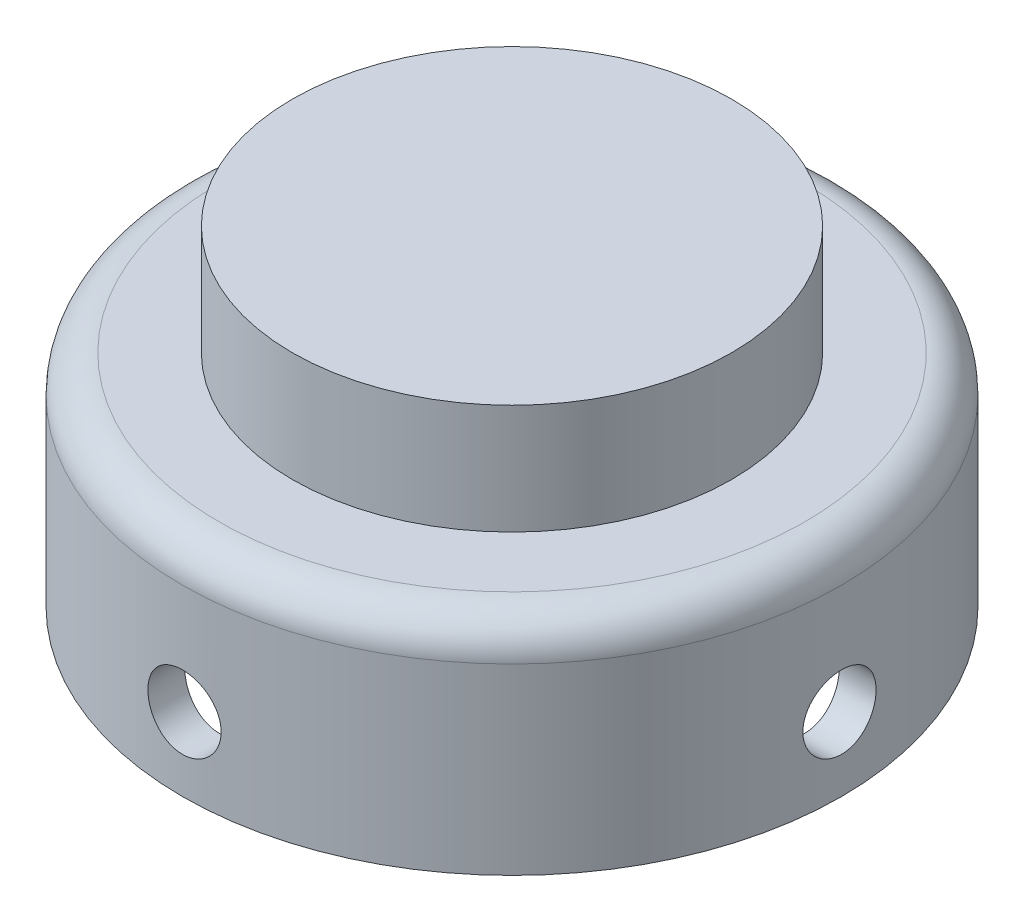
SolidWorks part; units mm, degrees
material "1060 Alloy"
ref_plane "Front Plane" through (0, 0, 0) normal (0, 0, 1) x (1, 0, 0)
ref_plane "Top Plane" through (0, 0, 0) normal (0, 1, 0) x (1, 0, 0)
ref_plane "Right Plane" through (0, 0, 0) normal (1, 0, 0) x (0, 0, -1)
sketch "Sketch1" plane through (0, 0, 0) normal (0, 1, 0) x (1, 0, 0)
  circle A0 centre (0, 0) radius 76.2
  dimension "D1" = 152.4
extrude "Boss-Extrude1" add sketch "Sketch1" along normal blind 38.1
sketch "Sketch2" plane through (0, 0, 0) normal (0, -1, 0) x (1, 0, 0)
  circle A0 centre (0, 0) radius 114.3
  dimension "D1" = 228.6
extrude "Boss-Extrude2" add sketch "Sketch2" along normal blind 76.2
fillet "Fillet2" radius 12.7 1 edges at (0, 0, -114.3)
sketch "Sketch3" plane through (0, -76.2, 0) normal (0, -1, 0) x (1, 0, 0)
  circle A0 centre (0, 0) radius 101.6
  dimension "D1" = 203.2
extrude "Cut-Extrude1" cut sketch "Sketch3" against normal blind 50.8
sketch "Sketch4" plane through (0, 0, 0) normal (1, 0, 0) x (0, 0, -1)
  line L1 (76.2, 0) -> (-76.2, 0) construction
  line L2 (-114.3, -76.2) -> (114.3, -76.2) construction
  circle A0 centre (0, -50.8) radius 12.7
  circle A1 centre (69.85, -50.8) radius 12.7
  circle A2 centre (-69.7917, -50.8) radius 12.7
  dimension "D1" = 25.4
  dimension "D2" = 25.4
  dimension "D3" = 25.4
  dimension "D4" = 69.7917
  dimension "D5" = 69.85
  dimension "D6" = 25.4
  dimension "D7" = 50.8
extrude "Cut-Extrude2" cut sketch "Sketch4" against normal through all and the other way through all contours A0
sketch "Sketch5" plane through (0, 0, 0) normal (0, 0, 1) x (1, 0, 0)
  line L2 (-114.3, -76.2) -> (114.3, -76.2) construction
  circle A0 centre (0, -50.8) radius 12.7
  dimension "D1" = 25.4
  dimension "D2" = 25.4
extrude "Cut-Extrude3" cut sketch "Sketch5" against normal through all and the other way through all
